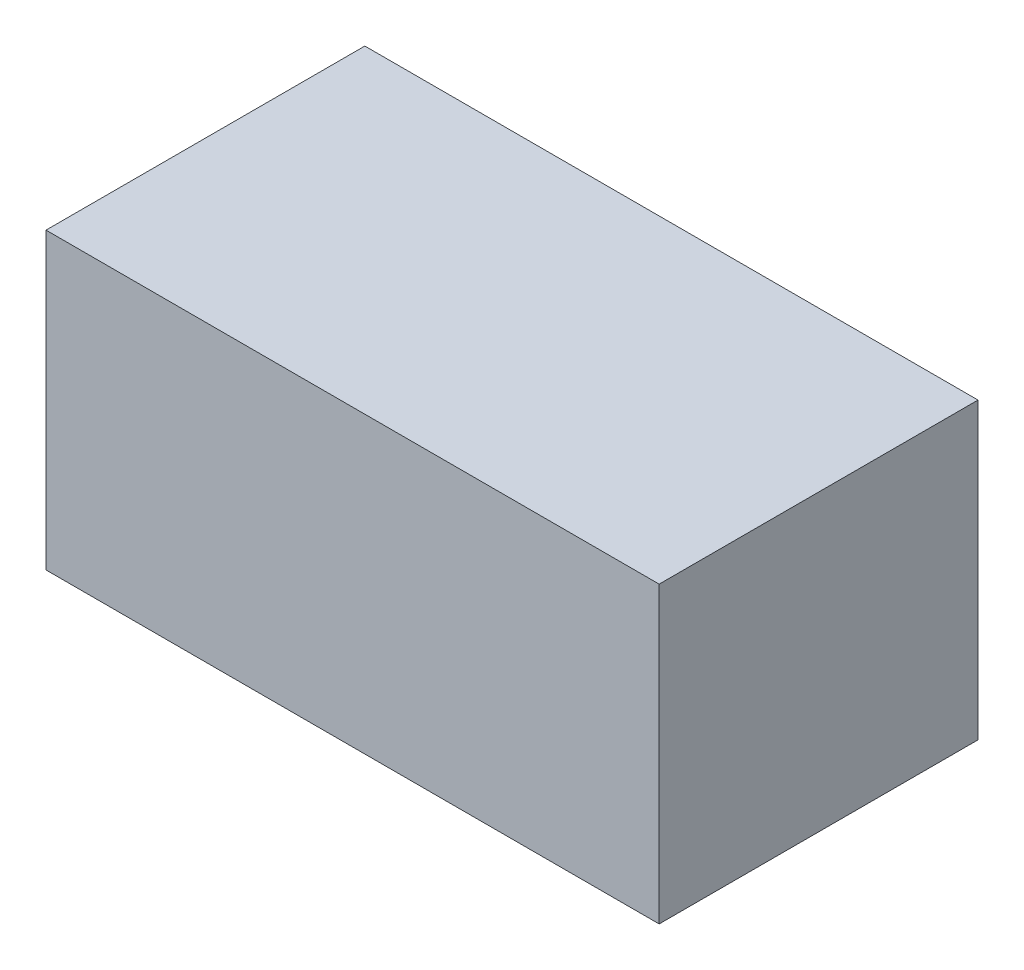
SolidWorks part; units mm, degrees
ref_plane "Front Plane" through (0, 0, 0) normal (0, 0, 1) x (1, 0, 0)
ref_plane "Top Plane" through (0, 0, 0) normal (0, 1, 0) x (1, 0, 0)
ref_plane "Right Plane" through (0, 0, 0) normal (1, 0, 0) x (0, 0, -1)
sketch "Sketch1" plane through (0, 0, 0) normal (0, 1, 0) x (1, 0, 0)
  line L1 (-62.5, -32.5) -> (62.5, -32.5)
  line L2 (-62.5, -32.5) -> (-62.5, 32.5)
  line L3 (-62.5, 32.5) -> (62.5, 32.5)
  line L4 (62.5, -32.5) -> (62.5, 32.5)
  line L5 (-62.5, -32.5) -> (62.5, 32.5) construction
  line L6 (-62.5, 32.5) -> (62.5, -32.5) construction
  point P0 (0, 0)
  dimension "D1" = 65
  dimension "D2" = 125
extrude "Boss-Extrude1" add sketch "Sketch1" along normal blind 60
